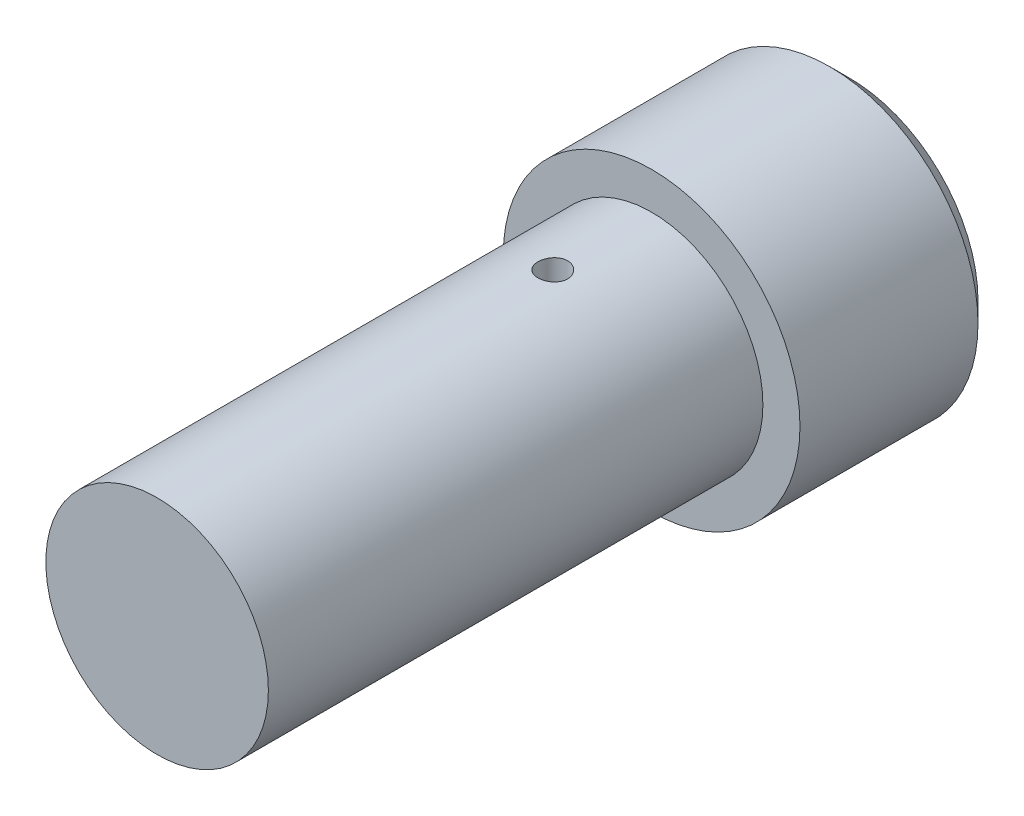
SolidWorks part; units mm, degrees
material "PW80:Mi:0:32:C1:0:1:2:Re:8:"
ref_plane "Plan1" through (0, 0, 0) normal (0, 0, 1) x (1, 0, 0)
ref_plane "Plan2" through (0, 0, 0) normal (0, 1, 0) x (1, 0, 0)
ref_plane "Plan3" through (0, 0, 0) normal (1, 0, 0) x (0, 0, -1)
sketch "Esquisse1" plane through (0, 0, 0) normal (0, 0, 1) x (1, 0, 0)
  circle A0 centre (0, 0) radius 30
extrude "Base-Extrusion" add sketch "Esquisse1" along normal blind 40
sketch "Esquisse2" plane through (0, 0, 40) normal (0, 0, 1) x (1, 0, 0)
  circle A0 centre (0, 0) radius 22.5
extrude "Boss.-Extru.1" add sketch "Esquisse2" along normal blind 100
ref_plane "Plan4" through (0, 30, 0) normal (0, 1, 0) x (-1, 0, 0)
sketch "Esquisse3" plane through (0, 30, 0) normal (0, 1, 0) x (-1, 0, 0)
  line L0 (0, 40) -> (0, 0) construction
  circle A0 centre (0, 60) radius 3
extrude "Enlèv. mat.-Extru.1" cut sketch "Esquisse3" against normal blind 30
chamfer "Chanfrein1" distance 4 angle 45
